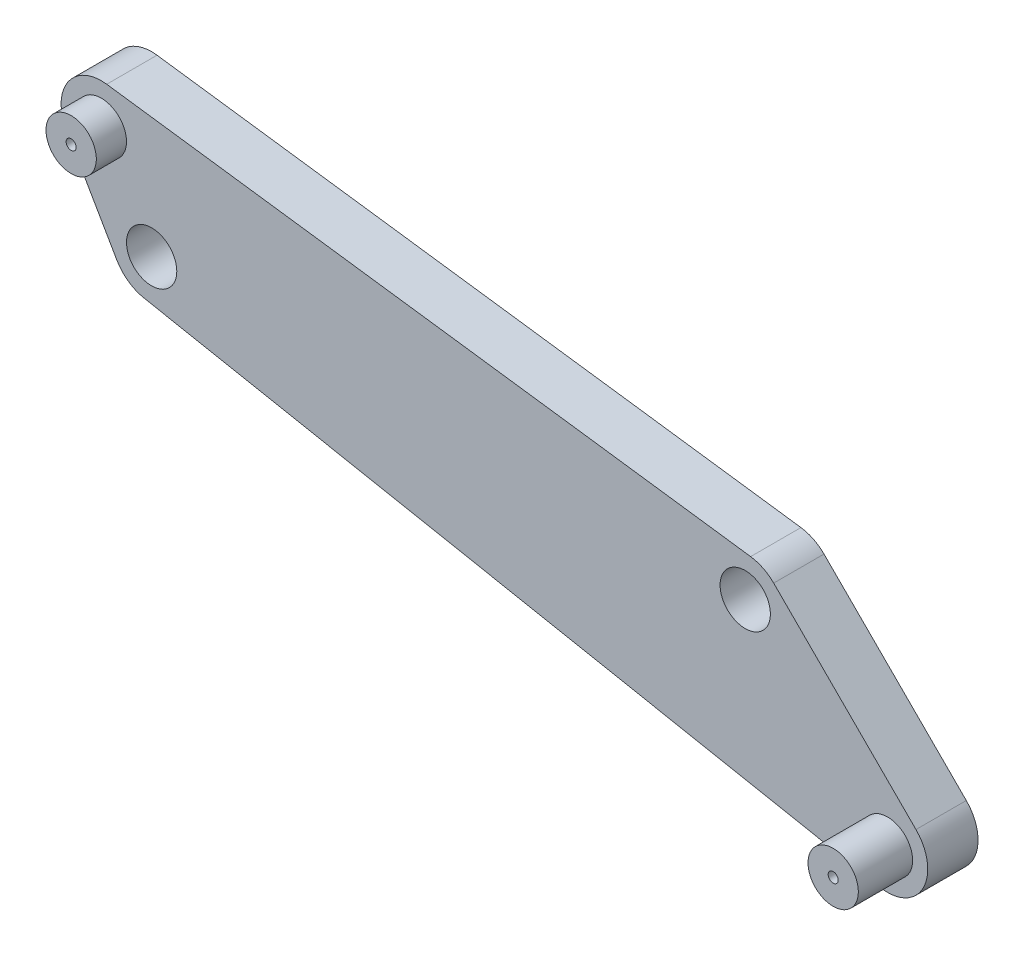
SolidWorks part; units mm, degrees
material "ABS"
ref_plane "Front Plane" through (0, 0, 0) normal (0, 0, 1) x (1, 0, 0)
ref_plane "Top Plane" through (0, 0, 0) normal (0, 1, 0) x (1, 0, 0)
ref_plane "Right Plane" through (0, 0, 0) normal (1, 0, 0) x (0, 0, -1)
sketch "Sketch1" plane through (0, 0, 0) normal (0, 0, 1) x (1, 0, 0)
  line L0 (0, 0) -> (-59, 0)
  line L1 (-59, 0) -> (-64, 8.6603)
  line L2 (0, 0) -> (14.1421, -14.1421)
  dimension "D1" = 59
  dimension "D2" = 10
  dimension "D3" = 20
  dimension "D4" = 120
  dimension "D5" = 135
sketch "Sketch2" plane through (0, 0, 0) normal (0, 0, 1) x (1, 0, 0)
  line L0 (-63.4636, 12.6241) -> (0.5364, 3.9639)
  line L1 (2.8284, 2.8284) -> (16.9706, -11.3137)
  line L2 (13.3828, -18.0694) -> (-59.7593, -3.9273)
  line L3 (-62.4641, -2) -> (-67.4641, 6.6603)
  circle A0 centre (-59, 0) radius 2.5
  circle A1 centre (-64, 8.6603) radius 2.5
  arc A2 (-63.4636, 12.6241) -> (-67.4641, 6.6603) centre (-64, 8.6603) ccw
  arc A3 (-62.4641, -2) -> (-59.7593, -3.9273) centre (-59, 0) ccw
  circle A4 centre (0, 0) radius 2.5
  circle A5 centre (14.1421, -14.1421) radius 2.5
  arc A6 (2.8284, 2.8284) -> (0.5364, 3.9639) centre (0, 0) ccw
  arc A7 (13.3828, -18.0694) -> (16.9706, -11.3137) centre (14.1421, -14.1421) ccw
  dimension "D1" = 5
  dimension "D2" = 5
  dimension "D3" = 5
  dimension "D4" = 5
  dimension "D5" = 8
  dimension "D6" = 8
  dimension "D7" = 8
  dimension "D8" = 8
extrude "Boss-Extrude1" add sketch "Sketch2" along normal blind 5
sketch "Sketch4" plane through (0, 0, 0) normal (0, 0, -1) x (-1, 0, 0)
  circle A0 centre (64, 8.6603) radius 2.5
  circle A1 centre (64, 8.6603) radius 0.5
  circle A2 centre (-14.1421, -14.1421) radius 2.5
  circle A3 centre (-14.1421, -14.1421) radius 0.5
  dimension "D1" = 1
  dimension "D2" = 5
  dimension "D3" = 5
  dimension "D4" = 1
extrude "Boss-Extrude3" add sketch "Sketch4" against normal blind 8
sketch "Sketch5" plane through (0, 0, 8) normal (0, 0, 1) x (1, 0, 0)
  circle A0 centre (14.1421, -14.1421) radius 2.5
  circle A1 centre (14.1421, -14.1421) radius 0.5
  dimension "D1" = 5
  dimension "D2" = 1
extrude "Boss-Extrude4" add sketch "Sketch5" along normal blind 2.4
